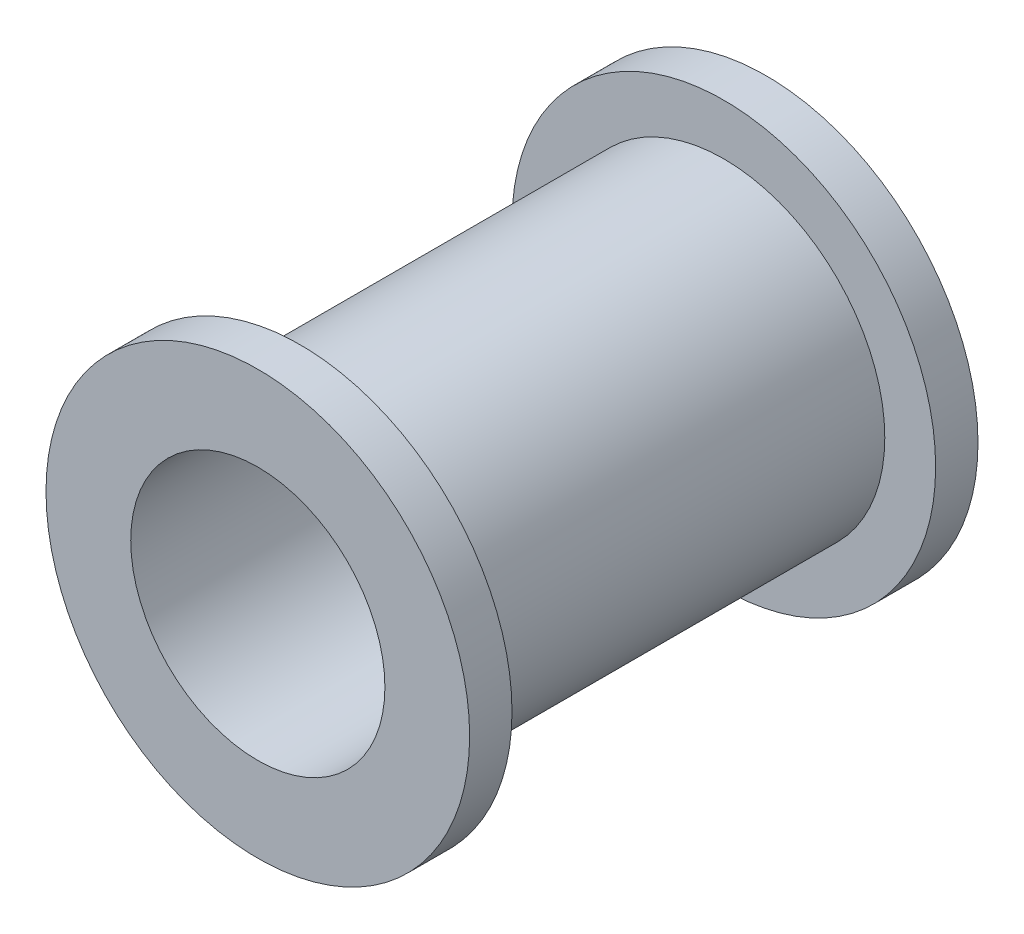
SolidWorks part; units mm, degrees
material "Alloy Steel"
ref_plane "Front Plane" through (0, 0, 0) normal (0, 0, 1) x (1, 0, 0)
ref_plane "Top Plane" through (0, 0, 0) normal (0, 1, 0) x (1, 0, 0)
ref_plane "Right Plane" through (0, 0, 0) normal (1, 0, 0) x (0, 0, -1)
sketch "Sketch1" plane through (0, 0, 0) normal (0, 0, 1) x (1, 0, 0)
  circle A0 centre (0, 0) radius 19
  circle A1 centre (0, 0) radius 15
extrude "Boss-Extrude1" add sketch "Sketch1" along normal blind 50
sketch "Sketch2" plane through (0, 0, 50) normal (0, 0, 1) x (1, 0, 0)
  circle A0 centre (0, 0) radius 25
  circle A1 centre (0, 0) radius 15
extrude "Boss-Extrude2" add sketch "Sketch2" along normal blind 5
sketch "Sketch4" plane through (0, 0, 0) normal (0, 0, -1) x (-1, 0, 0)
  circle A0 centre (0, 0) radius 15
  circle A1 centre (0, 0) radius 25
extrude "Boss-Extrude3" add sketch "Sketch4" along normal blind 5
